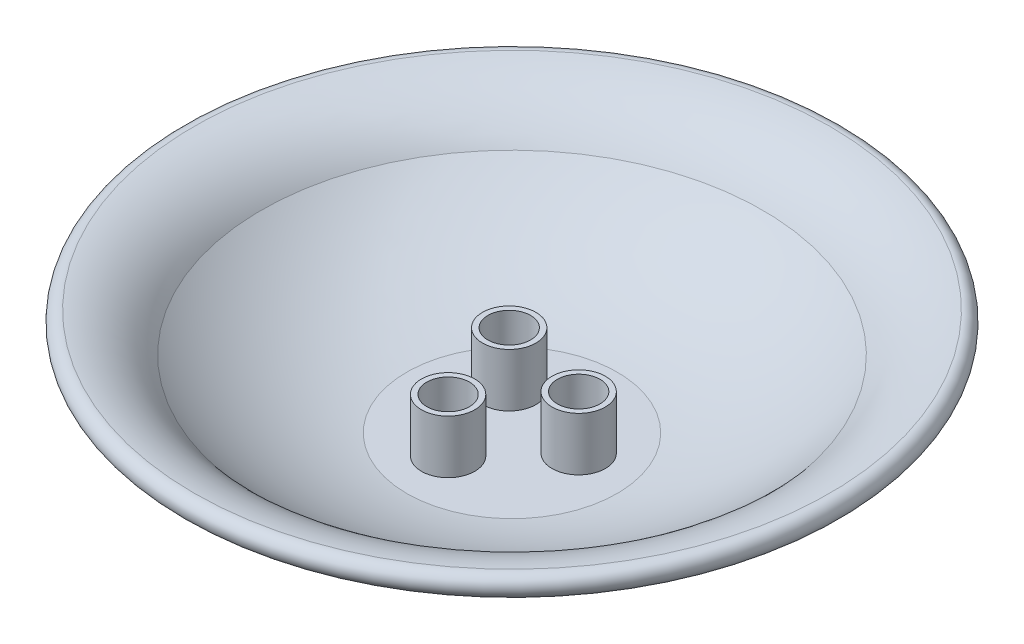
SolidWorks part; units mm, degrees
ref_plane "Front Plane" through (0, 0, 0) normal (0, 0, 1) x (1, 0, 0)
ref_plane "Top Plane" through (0, 0, 0) normal (0, 1, 0) x (1, 0, 0)
ref_plane "Right Plane" through (0, 0, 0) normal (1, 0, 0) x (0, 0, -1)
sketch "Sketch1" plane through (0, 0, 0) normal (0, 0, 1) x (1, 0, 0)
  line L3 (3.1193, -4.8165) -> (13.1193, -4.8165)
  line L6 (3.2579, -2.8165) -> (13.1193, -2.8165)
  line L7 (13.1193, -2.8165) -> (13.1193, -4.8165)
  arc A0 (-16.8807, 5.1835) -> (-11.8807, 2.1835) centre (-17.5986, -1.6796) cw
  arc A1 (3.1193, -4.8165) -> (-11.8807, 2.1835) centre (6.9048, 22.8668) cw
  arc A2 (-16.6727, 7.1726) -> (-10.3722, 3.5164) centre (-17.5986, -1.6796) cw
  arc A3 (3.2579, -2.8165) -> (-10.3722, 3.5164) centre (6.9048, 22.8668) cw
  arc A4 (-16.8807, 5.1835) -> (-16.6727, 7.1726) centre (-16.7767, 6.1781) cw
  dimension "D1" = 2
  dimension "D5" = 10
revolve "Revolve1" add sketch "Sketch1" angle 360 about L7
sketch "Sketch2" plane through (0, -2.8165, 0) normal (0, 1, 0) x (1, 0, 0)
  circle A0 centre (9.4558, 3.4028) radius 2.5
  circle A1 centre (13.1193, 0) radius 9.8613 construction
  circle A2 centre (9.4558, 3.4028) radius 2
  circle A3 centre (17.8979, 1.4713) radius 2.5
  circle A4 centre (17.8979, 1.4713) radius 2
  circle A5 centre (12.0041, -4.8741) radius 2.5
  circle A6 centre (12.0041, -4.8741) radius 2
  dimension "D1" = 5
  dimension "D2" = 5
  dimension "D3" = 4
  dimension "D4" = 3
extrude "Boss-Extrude2" add sketch "Sketch2" along normal blind 5
sketch "Sketch3" plane through (0, -2.8165, 0) normal (0, 1, 0) x (1, 0, 0)
  circle A0 centre (17.8979, 1.4713) radius 2
  circle A1 centre (12.0041, -4.8741) radius 2
  circle A2 centre (9.4558, 3.4028) radius 2
extrude "Cut-Extrude1" cut sketch "Sketch3" against normal blind 5
